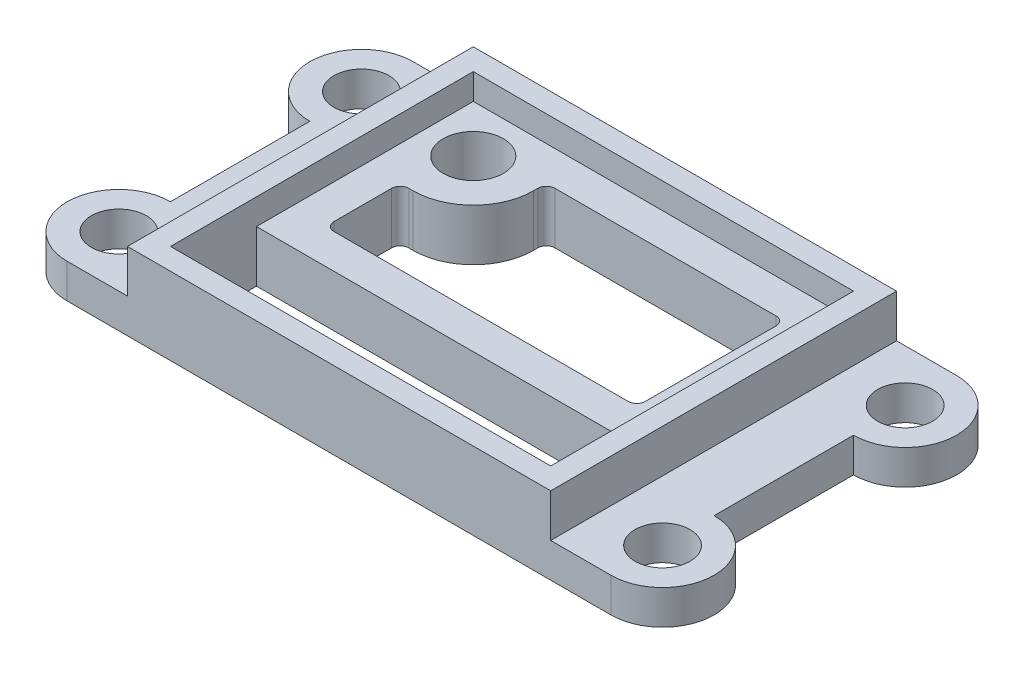
SolidWorks part; units mm, degrees
ref_plane "Front Plane" through (0, 0, 0) normal (0, 0, 1) x (1, 0, 0)
ref_plane "Top Plane" through (0, 0, 0) normal (0, 1, 0) x (1, 0, 0)
ref_plane "Right Plane" through (0, 0, 0) normal (1, 0, 0) x (0, 0, -1)
sketch "Sketch1" plane through (0, 0, 0) normal (0, 1, 0) x (1, 0, 0)
  line L0 (-12.3, 10.05) -> (-12.3, -10.05)
  line L1 (-10.8, 8.55) -> (10.8, 8.55) construction
  line L2 (-10.8, 8.55) -> (-10.8, -8.55) construction
  line L3 (-10.8, -8.55) -> (10.8, -8.55) construction
  line L4 (10.8, 8.55) -> (10.8, -8.55) construction
  line L5 (-12.3, -10.05) -> (12.3, -10.05)
  line L6 (12.3, 10.05) -> (12.3, -10.05)
  line L7 (-12.3, 10.05) -> (12.3, 10.05)
  circle A0 centre (-8.3, 6.05) radius 1.75
  point P4 (0, 8.55)
  point P6 (-10.8, 0)
  point P9 (-8.4609, 6.1473)
  dimension "D3" = 3.5
  dimension "D1" = 21.6
  dimension "D2" = 17.1
  dimension "D4" = 2.5
  dimension "D5" = 2.5
  dimension "D6" = 1.5
extrude "Boss-Extrude1" add sketch "Sketch1" along normal blind 1.5
sketch "Sketch2" plane through (0, 1.5, 0) normal (0, 1, 0) x (1, 0, 0)
  line L0 (-11.05, 8.8) -> (-11.05, -8.8)
  line L1 (-12.3, 10.05) -> (12.3, 10.05)
  line L2 (-12.3, 10.05) -> (-12.3, -10.05)
  line L3 (-12.3, -10.05) -> (12.3, -10.05)
  line L4 (12.3, 10.05) -> (12.3, -10.05)
  line L5 (-11.05, -8.8) -> (11.05, -8.8)
  line L6 (11.05, 8.8) -> (11.05, -8.8)
  line L7 (-11.05, 8.8) -> (11.05, 8.8)
  dimension "D1" = 1.25
extrude "Boss-Extrude2" add sketch "Sketch2" along normal blind 3
sketch "Sketch3" plane through (0, 1.5, 0) normal (0, 1, 0) x (1, 0, 0)
  line L0 (11.05, -8.8) -> (11.05, 8.8) construction
  line L1 (-11.05, 8.8) -> (11.05, 8.8)
  line L2 (-11.05, 8.8) -> (-11.05, -3.8)
  line L3 (-11.05, -3.8) -> (11.05, -3.8)
  line L4 (11.05, 8.8) -> (11.05, -3.8)
  line L5 (-11.05, -8.8) -> (11.05, -8.8) construction
  circle A0 centre (-8.3, 6.05) radius 1.75
  dimension "D1" = 5
extrude "Boss-Extrude3" add sketch "Sketch3" along normal blind 1.5
sketch "Sketch4" plane through (0, 0, 0) normal (0, 1, 0) x (1, 0, 0)
  line L0 (12.3, -10.05) -> (12.3, 10.05) construction
  line L1 (15.8, 10.05) -> (12.3, 10.05)
  line L2 (15.8, 4.05) -> (12.3, 4.05)
  line L3 (12.3, -10.05) -> (12.3, 10.05) construction
  line L4 (12.3, 10.05) -> (12.3, 4.05)
  line L5 (0, 10.05) -> (0, -10.05) construction
  line L6 (12.3, 10.05) -> (-12.3, 10.05) construction
  line L7 (-12.3, -10.05) -> (12.3, -10.05) construction
  line L8 (-12.3, 0) -> (12.3, 0) construction
  line L9 (-12.3, 10.05) -> (-12.3, -10.05) construction
  line L10 (-15.8, 4.05) -> (-12.3, 4.05)
  line L11 (-12.3, 10.05) -> (-12.3, 4.05)
  line L12 (-15.8, 10.05) -> (-12.3, 10.05)
  line L13 (15.8, -4.05) -> (12.3, -4.05)
  line L14 (12.3, -10.05) -> (12.3, -4.05)
  line L15 (15.8, -10.05) -> (12.3, -10.05)
  line L16 (-15.8, -10.05) -> (-12.3, -10.05)
  line L17 (-12.3, -10.05) -> (-12.3, -4.05)
  line L18 (-15.8, -4.05) -> (-12.3, -4.05)
  circle A0 centre (15.8, 7.05) radius 1.6
  arc A1 (15.8, 4.05) -> (15.8, 10.05) centre (15.8, 7.05) ccw
  circle A2 centre (-15.8, 7.05) radius 1.6
  arc A3 (-15.8, 4.05) -> (-15.8, 10.05) centre (-15.8, 7.05) cw
  arc A4 (15.8, -4.05) -> (15.8, -10.05) centre (15.8, -7.05) cw
  circle A5 centre (15.8, -7.05) radius 1.6
  circle A6 centre (-15.8, -7.05) radius 1.6
  arc A7 (-15.8, -4.05) -> (-15.8, -10.05) centre (-15.8, -7.05) ccw
  dimension "D1" = 3.2
  dimension "D3" = 6
  dimension "D2" = 3.5
extrude "Boss-Extrude4" add sketch "Sketch4" along normal blind 2
sketch "Sketch5" plane through (0, 3, 0) normal (0, 1, 0) x (1, 0, 0)
  line L1 (-10.05, 7.8) -> (10.05, 7.8) construction
  line L2 (-10.05, 7.8) -> (-10.05, -2.8) construction
  line L3 (-10.05, -2.8) -> (10.05, -2.8) construction
  line L4 (10.05, 7.8) -> (10.05, -2.8) construction
  line L5 (-11.05, -3.8) -> (11.05, -3.8) construction
  line L6 (-9.05, 6.8) -> (-9.05, -1.8) construction
  line L7 (-9.05, -1.8) -> (9.05, -1.8) construction
  line L8 (9.05, 6.8) -> (9.05, -1.8) construction
  line L9 (-9.05, 6.8) -> (9.05, 6.8) construction
  line L10 (-9.05, -1.3) -> (-9.05, 2.05)
  line L11 (-8.55, 2.55) -> (-8.3, 2.55)
  line L12 (-4.8, 6.05) -> (-4.8, 6.3)
  line L13 (-4.3, 6.8) -> (8.55, 6.8)
  line L14 (9.05, 6.3) -> (9.05, -1.3)
  line L15 (8.55, -1.8) -> (-8.55, -1.8)
  circle A0 centre (-8.3, 6.05) radius 1.75 construction
  arc A1 (-8.3, 2.55) -> (-4.8, 6.05) centre (-8.3, 6.05) ccw
  arc A2 (-4.8, 6.3) -> (-4.3, 6.8) centre (-4.3, 6.3) cw
  arc A3 (8.55, 6.8) -> (9.05, 6.3) centre (8.55, 6.3) cw
  arc A4 (9.05, -1.3) -> (8.55, -1.8) centre (8.55, -1.3) cw
  arc A5 (-9.05, -1.3) -> (-8.55, -1.8) centre (-8.55, -1.3) ccw
  arc A6 (-9.05, 2.05) -> (-8.55, 2.55) centre (-8.55, 2.05) cw
  point P4 (0, -2.8)
  point P17 (0, 0)
  point P18 (-5.4265, 3.1765)
  point P23 (-4.8, 6.8)
  dimension "D4" = 3.5
  dimension "D5" = 0.5
  dimension "D1" = 1
  dimension "D3" = 3.5
  dimension "D2" = 1
extrude "Cut-Extrude1" cut sketch "Sketch5" against normal through all
sketch "Sketch6" plane through (0, 1.5, 0) normal (0, 1, 0) x (1, 0, 0)
  line L1 (-11.05, -3.8) -> (11.05, -3.8)
  line L2 (-11.05, -3.8) -> (-11.05, -8.8)
  line L3 (-11.05, -8.8) -> (11.05, -8.8)
  line L4 (11.05, -3.8) -> (11.05, -8.8)
extrude "Cut-Extrude2" cut sketch "Sketch6" against normal through all
sketch "Sketch8" plane through (0, 2, 0) normal (0, 1, 0) x (1, 0, 0)
  line L1 (-15.8, 4.05) -> (-12.3, 4.05)
  line L2 (-15.8, 4.05) -> (-15.8, -4.05)
  line L3 (-15.8, -4.05) -> (-12.3, -4.05)
  line L4 (-12.3, 4.05) -> (-12.3, -4.05)
  line L5 (15.8, 4.05) -> (12.3, 4.05)
  line L6 (15.8, 4.05) -> (15.8, -4.05)
  line L7 (15.8, -4.05) -> (12.3, -4.05)
  line L8 (12.3, 4.05) -> (12.3, -4.05)
extrude "Boss-Extrude5" add sketch "Sketch8" against normal through all
